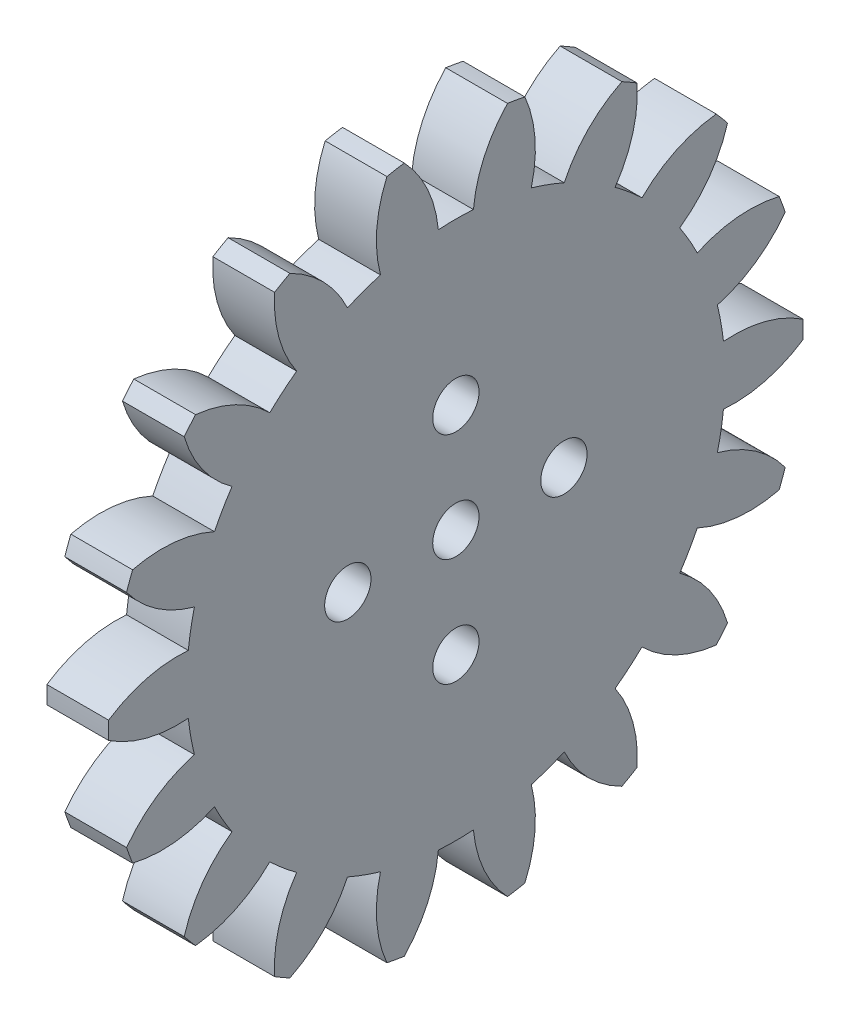
SolidWorks part; units mm, degrees
ref_plane "Plane1" through (0, 0, 0) normal (0, 0, 1) x (1, 0, 0)
ref_plane "Plane2" through (0, 0, 0) normal (0, 1, 0) x (1, 0, 0)
ref_plane "Plane3" through (0, 0, 0) normal (1, 0, 0) x (0, 0, -1)
other "Configuration Table"
sketch "HoldingSke" plane through (0, 0, 0) normal (0, 1, 0) x (1, 0, 0)
  line L0 (0, 0) -> (0.4227, -0.1373)
  line L1 (-15, 0) -> (100, 0) construction
  line L2 (0, 0) -> (-2.1039, 2.3779)
  line L3 (0, 0) -> (-11.863, 4.5341)
  line L4 (0, 0) -> (8.2133, 2.6687)
  line L5 (0, 0) -> (-46.8476, -17.4728)
  line L6 (0, 0) -> (-3.3159, -2.2372)
  line L7 (-2.1039, 2.3779) -> (8.6586, 51.2059)
  line L8 (-76.2, 54.61) -> (-75.7, 54.61)
  line L9 (-71.009, 38.7566) -> (-53.1078, 45.2721)
  line L10 (-76.2, 71.12) -> (104.1128, 71.12)
  line L11 (0, 0) -> (-4, 0)
  line L12 (-76.2, 101.6) -> (-76.123, 101.6)
  line L13 (24.9733, 27.94) -> (52.9518, 28.4284)
  line L14 (24.9733, 27.94) -> (24.9743, 27.94)
  line L15 (24.9733, 27.94) -> (100.4006, 29.5858)
  line L16 (-63.627, -2.25) -> (-12.827, -2.25)
  circle A0 centre (0, 0) radius 1.5
  circle A1 centre (0, 0) radius 17.4365
  circle A2 centre (0, 0) radius 37.5
  circle A3 centre (0, 0) radius 1.5
  dimension "MHD" = 34.873
  dimension "Hub_dia" = 75
  dimension "Bore" = 3
  dimension "MBD" = 3
  dimension "Num_teeth" = 18
  dimension "Pitch" = 0.4444
  dimension "Overall_len" = 50
  dimension "Show_teeth" = 18
  dimension "Thickness" = 4
  dimension "OAL" = 50.0001
  dimension "T_dim" = 0.5
  dimension "Ap" = 20
  dimension "H" = 19.05
  dimension "Pitch_radius" = 180.3128
  dimension "Width" = 4
  dimension "Backlash" = 0.077
  dimension "Addendum_fac" = 1
  dimension "Dedendum_fac" = 1.25
  dimension "Clearance_fac" = 0.25
  dimension "Dedendum_add" = 0.001
  dimension "Module" = 2.25
sketch "BasProSke" plane through (0, 0, 0) normal (0, 1, 0) x (1, 0, 0)
  line L0 (-10, 0) -> (60, 0) construction
  line L1 (0, 0) -> (0, 22.5)
  line L2 (0, 0) -> (4, 0)
  line L3 (4, 0) -> (4, 22.5)
  line L4 (4, 22.5) -> (0, 22.5)
  dimension "Thickness" = 4
  dimension "Diameter" = 45
revolve "Base-Revolve" add sketch "BasProSke" angle 360 about L0
sketch "TooCutSke" plane through (0, 0, 0) normal (1, 0, 0) x (0, 0, -1)
  line L1 (0, 0) -> (0, 107) construction
  line L2 (0, 0) -> (-1.8996, 20.1607) construction
  line L3 (0, 0) -> (-7.0099, 39.7553) construction
  line L4 (-1.8996, 20.1607) -> (-3.505, 19.8776) construction
  arc A0 (1.1362, 17.3994) -> (-1.1362, 17.3994) centre (0, 0) ccw
  arc A1 (3.3657, 22.2725) -> (-3.3657, 22.2725) centre (0, 0) ccw
  circle A2 centre (0, 0) radius 20.25 construction
  circle A3 centre (0, 0) radius 19.0288 construction
  arc A4 (-1.1362, 17.3994) -> (-3.3657, 22.2725) centre (-9.202, 16.6558) ccw
  arc A5 (3.3657, 22.2725) -> (1.1362, 17.3994) centre (9.202, 16.6558) ccw
  dimension "Root_dia" = 34.873
  dimension "Overcut_dia" = 45.0508
  dimension "Pitch_dia" = 40.5
  dimension "Base_dia" = 38.0576
  dimension "Flank_rad" = 8.1
  dimension "Half_ang" = 10
  dimension "Half_CT" = 1.6302
extrude "ToothCut" cut sketch "TooCutSke" along normal through all
fillet "Breaks" [suppressed] radius 0.045
fillet "RootFillets" [suppressed] radius 0.5635
pattern_circular "TeethCuts" count 18 every 20 about axis through (-10, 0, 0) along (1, 0, 0) of "ToothCut", "RootFillets", "Breaks"
sketch "HubNeaOneSke" plane through (0, 0, 0) normal (-1, 0, 0) x (0, 0, 1)
  circle A0 centre (0, 0) radius 17.4365
  dimension "Diameter" = 34.873
extrude "HubNearOne" [suppressed] add sketch "HubNeaOneSke" along normal blind 46.0001
sketch "HubNeaBotSke" plane through (0, 0, 0) normal (-1, 0, 0) x (0, 0, 1)
  circle A0 centre (0, 0) radius 17.4365
  dimension "Diameter" = 34.873
extrude "HubNearBoth" [suppressed] add sketch "HubNeaBotSke" along normal blind 23
ref_plane "FarPln" through (4, 0, 0) normal (1, 0, 0) x (0, 0, -1)
sketch "HubFarSke" plane through (4, 0, 0) normal (1, 0, 0) x (0, 0, -1)
  circle A0 centre (0, 0) radius 17.4365
  dimension "Diameter" = 34.873
extrude "HubFar" [suppressed] add sketch "HubFarSke" along normal blind 23
sketch "BorSke" plane through (0, 0, 0) normal (1, 0, 0) x (0, 0, -1)
  circle A0 centre (0, 0) radius 1.5
  dimension "Diameter" = 3
extrude "Bore" cut sketch "BorSke" along normal mid plane 100.0001
sketch "KeySke" plane through (0, 0, 0) normal (1, 0, 0) x (0, 0, -1)
  line L0 (-0.6, 0) -> (-0.6, 2)
  line L1 (-0.6, 2) -> (0.6, 2)
  line L2 (0.6, 2) -> (0.6, 0)
  line L3 (0, 0) -> (0, 34) construction
  line L4 (-0.6, 0) -> (0.6, 0)
  dimension "Offset" = 2
  dimension "Width" = 1.2
extrude "Keyway" [suppressed] cut sketch "KeySke" along normal mid plane 100.0001
pattern_circular "Keyway2" [suppressed] count 2 every 90 about axis through (-10, 0, 0) along (1, 0, 0)
sketch "草图1" plane through (4, 0, 0) normal (1, 0, 0) x (0, 0, -1)
  circle A0 centre (0, 7) radius 1.5
  circle A1 centre (7, 0) radius 1.5
  circle A2 centre (-7, 0) radius 1.5
  circle A3 centre (0, -7) radius 1.5
  point P5 (0, 0)
  point P9 (0, 0)
extrude "切除-拉伸1" cut sketch "草图1" against normal through all
equation "' \"Module@HoldingSke\" = 6.35"
equation "' \"Num_teeth@HoldingSke\" = 12"
equation "' \"Ap@HoldingSke\" =  20"
equation "' \"Ap@HoldingSke\" = 20"
equation "' \"Width@HoldingSke\" = 0.5 * 25.4"
equation "' \"Hub_dia@HoldingSke\"= 1 * 25.4"
equation "' \"Hub_dia@HoldingSke\" = 1 * 25.4"
equation "' \"Overall_len@HoldingSke\" = 1.0 * 25.4"
equation "' \"Bore@HoldingSke\" = 0.75 * 25.4"
equation "' \"T_dim@HoldingSke\" = 0.1 * 25.4"
equation "' \"Width@KeySke\" = 0.25 * 25.4"
equation "' \"Show_teeth@HoldingSke\" = 13"
equation "' \"Backlash@HoldingSke\" = 0.009 * 25.4"
equation "' \"Addendum_fac@HoldingSke\" = 1.0"
equation "' \"Dedendum_fac@HoldingSke\" = 1.25"
equation "' \"Dedendum_add@HoldingSke\" = 0.00005 * 25.4"
equation "' \"Clearance_fac@HoldingSke\" = 0.25"
equation "\"Pitch@HoldingSke\" = 1 / \"Module@HoldingSke\""
equation "\"Overcut_dia@TooCutSke\" = (\"Num_teeth@HoldingSke\" + 2 * \"Addendum_fac@HoldingSke\") / \"Pitch@HoldingSke\" + 0.002 * 25.4"
equation "\"Pitch_dia@TooCutSke\" = \"Num_teeth@HoldingSke\" / \"Pitch@HoldingSke\""
equation "\"Base_dia@TooCutSke\" = \"Num_teeth@HoldingSke\" / \"Pitch@HoldingSke\" * cos((\"Ap@HoldingSke\"  * 3.14159265 / 180))"
equation "\"Root_dia@TooCutSke\" = (\"Num_teeth@HoldingSke\" + 2) / \"Pitch@HoldingSke\" - 2 * (\"Addendum_fac@HoldingSke\" + \"Dedendum_fac@HoldingSke\") / \"Pitch@HoldingSke\" - \"Dedendum_add@HoldingSke\" * 2"
equation "\"Half_ang@TooCutSke\" = 180 / \"Num_teeth@HoldingSke\""
equation "\"Half_CT@TooCutSke\" = \"Num_teeth@HoldingSke\" / \"Pitch@HoldingSke\" * sin((3.14159265 / 2 / \"Num_teeth@HoldingSke\")) / 2 - 7 * \"Backlash@HoldingSke\" / 4"
equation "\"Flank_rad@TooCutSke\" = \"Num_teeth@HoldingSke\" / \"Pitch@HoldingSke\" / 5"
equation "\"Radius@RootFillets\" = \"Clearance_fac@HoldingSke\" / \"Pitch@HoldingSke\" + \"Dedendum_add@HoldingSke\""
equation "\"Break_rad@Breaks\" = 0.02 / \"Pitch@HoldingSke\""
equation "\"Thickness@HoldingSke\" = \"Width@HoldingSke\""
equation "\"OAL@HoldingSke\" = \"Thickness@HoldingSke\""
equation "\"MHD@HoldingSke\" = (\"Num_teeth@HoldingSke\" + 2) / \"Pitch@HoldingSke\" - 2 * (\"Addendum_fac@HoldingSke\" + \"Dedendum_fac@HoldingSke\")  / \"Pitch@HoldingSke\" - \"Dedendum_add@HoldingSke\" * 2"
equation "\"MBD@HoldingSke\" = (\"Num_teeth@HoldingSke\" + 2) / \"Pitch@HoldingSke\" - 2 * (\"Addendum_fac@HoldingSke\" + \"Dedendum_fac@HoldingSke\")  / \"Pitch@HoldingSke\" - \"Dedendum_add@HoldingSke\" * 2 - 0.002 * 25.4"
equation "\"MHD@HoldingSke\" = ((sgn( \"MHD@HoldingSke\" - \"Hub_dia@HoldingSke\" )-1)*( \"MHD@HoldingSke\" - \"Hub_dia@HoldingSke\" ))/-2+ \"Hub_dia@HoldingSke\""
equation "\"MBD@HoldingSke\" = ((sgn( \"MBD@HoldingSke\" - \"Bore@HoldingSke\" )-1)*( \"MBD@HoldingSke\" - \"Bore@HoldingSke\" ))/-2+ \"Bore@HoldingSke\""
equation "\"OAL@HoldingSke\" = ((sgn( \"OAL@HoldingSke\" - \"Overall_len@HoldingSke\" )+1)*( \"OAL@HoldingSke\" - \"Overall_len@HoldingSke\" ))/2 + \"Overall_len@HoldingSke\" + 0.000002 * 25.4"
equation "\"Num_teeth@TeethCuts\" = int( \"Show_teeth@HoldingSke\" ) + 1"
equation "\"Num_teeth@TeethCuts\" = ((sgn( \"Num_teeth@TeethCuts\" - \"Num_teeth@HoldingSke\" )-1)*( \"Num_teeth@TeethCuts\" - \"Num_teeth@HoldingSke\" ))/-2+ \"Num_teeth@HoldingSke\""
equation "\"Num_teeth@TeethCuts\" = ((sgn( \"Num_teeth@TeethCuts\" - 2.0)+1)*( \"Num_teeth@TeethCuts\" - 2.0))/2 +2.0"
equation "\"Angle@TeethCuts\" = 360.0 / \"Num_teeth@HoldingSke\""
equation "\"Diameter@BasProSke\" = (\"Num_teeth@HoldingSke\" + 2 * \"Addendum_fac@HoldingSke\") / \"Pitch@HoldingSke\""
equation "\"Thickness@BasProSke\"  = \"Thickness@HoldingSke\""
equation "' \"Fillet_rad@BasProSke\" =  \"Thickness@HoldingSke\" * 0.05"
equation "' \"Fillet_rad@BasProSke\" = \"Thickness@HoldingSke\" * 0.05"
equation "\"MHD@HoldingSke\" = ((sgn( \"MHD@HoldingSke\" - \"Root_dia@TooCutSke\" )-1)*( \"MHD@HoldingSke\" - \"Root_dia@TooCutSke\" ))/-2+ \"Root_dia@TooCutSke\""
equation "\"Diameter@HubNeaOneSke\" = \"MHD@HoldingSke\""
equation "\"Length@HubNearOne\" = \"OAL@HoldingSke\" - \"Thickness@BasProSke\""
equation "\"Diameter@HubNeaBotSke\" = \"MHD@HoldingSke\""
equation "\"Length@HubNearBoth\" = ( \"OAL@HoldingSke\" - \"Thickness@BasProSke\" ) / 2.0"
equation "\"Thickness@FarPln\" = \"Thickness@BasProSke\""
equation "\"Diameter@HubFarSke\" = \"MHD@HoldingSke\""
equation "\"Length@HubFar\" = ( \"OAL@HoldingSke\" - \"Thickness@BasProSke\" ) / 2.0"
equation "\"Diameter@BorSke\" = \"MBD@HoldingSke\""
equation "\"D1@Bore\" = \"OAL@HoldingSke\" * 2.0"
equation "\"D1@Keyway\" = \"OAL@HoldingSke\" * 2.0"
equation "\"Offset@KeySke\" = \"T_dim@HoldingSke\" + \"MBD@HoldingSke\" / 2.0"
